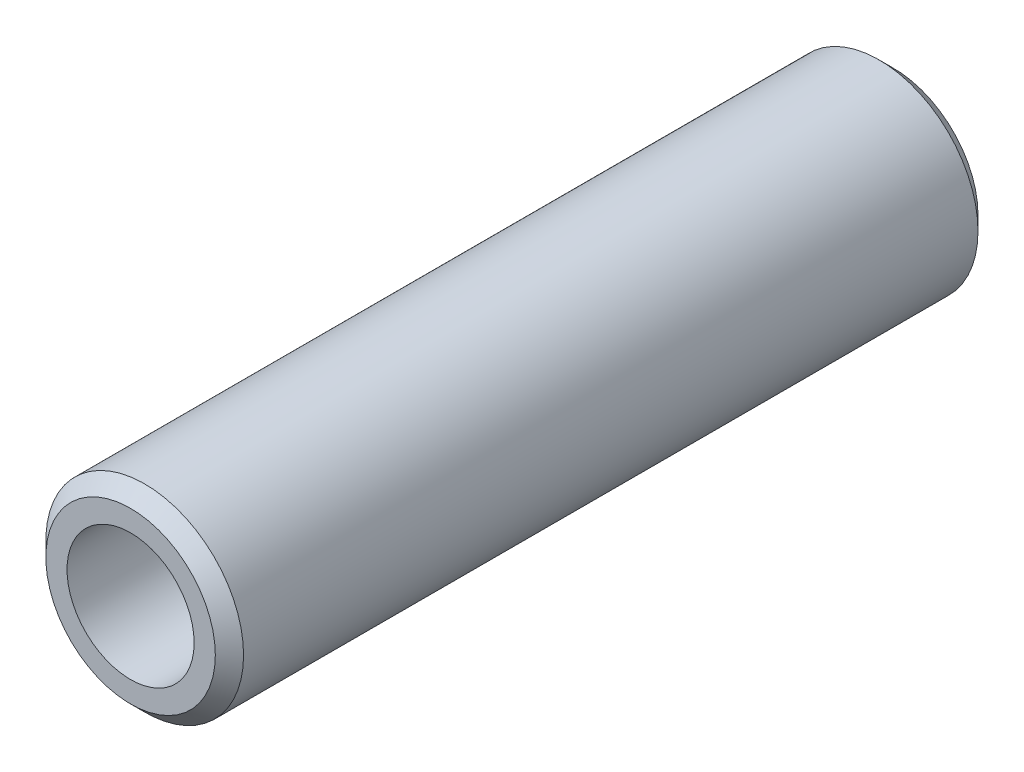
SolidWorks part; units mm, degrees
ref_plane "Plan de face" through (0, 0, 0) normal (0, 0, 1) x (1, 0, 0)
ref_plane "Plan de dessus" through (0, 0, 0) normal (0, 1, 0) x (1, 0, 0)
ref_plane "Plan de droite" through (0, 0, 0) normal (1, 0, 0) x (0, 0, -1)
sketch "Esquisse1" plane through (0, 0, 0) normal (0, 0, 1) x (1, 0, 0)
  circle A0 centre (0, 0) radius 22.5
  circle A1 centre (0, 0) radius 35
  dimension "D1" = 45
  dimension "D2" = 70
extrude "Boss.-Extru.1" add sketch "Esquisse1" along normal mid plane 270
chamfer "Chanfrein1" distance 5 angle 45 2 edges at (35, 0, -135) (35, 0, 135)
